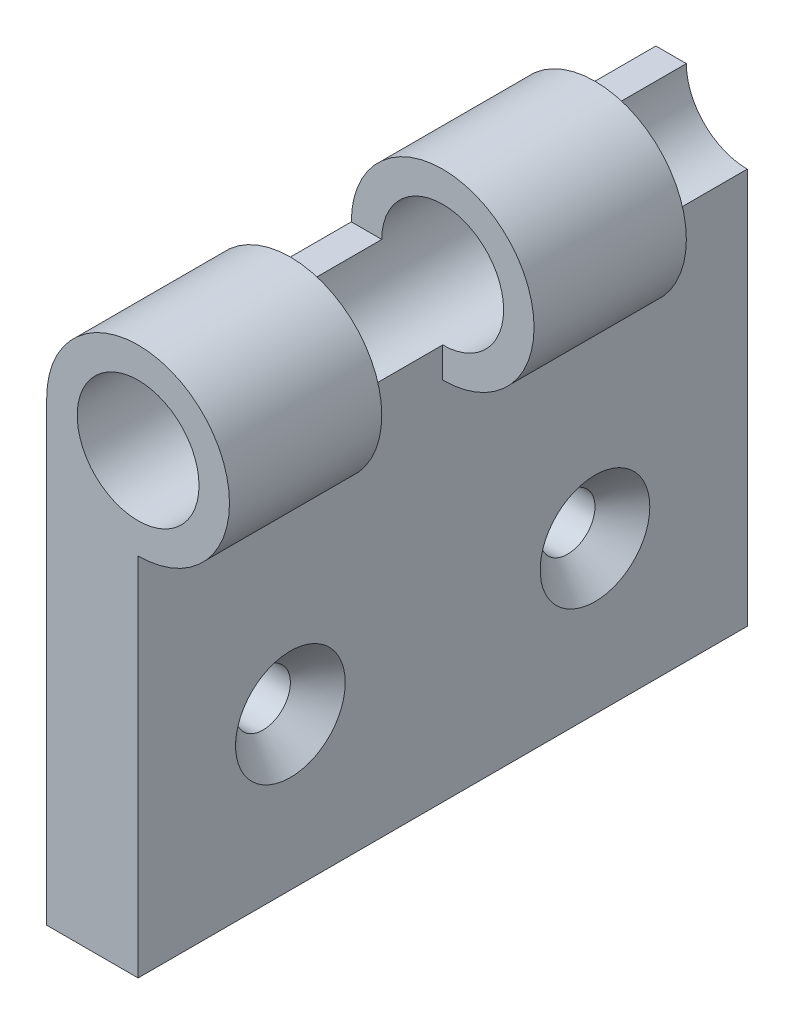
SolidWorks part; units mm, degrees
ref_plane "Front Plane" through (0, 0, 0) normal (0, 0, 1) x (1, 0, 0)
ref_plane "Top Plane" through (0, 0, 0) normal (0, 1, 0) x (1, 0, 0)
ref_plane "Right Plane" through (0, 0, 0) normal (1, 0, 0) x (0, 0, -1)
sketch "Sketch1" plane through (0, 0, 0) normal (0, 0, 1) x (1, 0, 0)
  line L1 (0, 0) -> (3, 0)
  line L2 (0, 0) -> (0, -15)
  line L3 (0, -15) -> (3, -15)
  line L4 (3, 0) -> (3, -15)
  dimension "D1" = 3
  dimension "D2" = 15
extrude "Boss-Extrude1" add sketch "Sketch1" against normal blind 20
sketch "Sketch2" plane through (0, 0, 0) normal (0, 0, 1) x (1, 0, 0)
  circle A0 centre (3, 0) radius 3
  dimension "D1" = 6
extrude "Boss-Extrude2" add sketch "Sketch2" against normal blind 5
pattern_linear "LPattern2" count 2 spacing 10 along (0, 0, -1) of "Boss-Extrude2"
sketch "Sketch3" plane through (0, 0, 0) normal (0, 0, 1) x (1, 0, 0)
  circle A0 centre (3, 0) radius 2
  dimension "D1" = 4
  dimension "D2" = 3
extrude "Cut-Extrude1" cut sketch "Sketch3" against normal through all both and the other way through all
hole_wizard "CSK for M1.6 Countersunk Flat Head Screw1" positions "Sketch5" profile "Sketch6" countersink size "M1.6" standard "ISO"
sketch "Sketch5" plane through (3, 0, 0) normal (1, 0, 0) x (0, 0, -1)
  line L0 (0, -15) -> (0, -3) construction
  line L1 (20, -15) -> (0, -15) construction
  point P0 (5, -10)
  point P6 (15, -10)
  dimension "D1" = 5
  dimension "D2" = 10
  dimension "D3" = 5
sketch "Sketch6" plane through (3, -10, -5) normal (0, 1, 0) x (0, 0, -1)
  line L0 (0, 0) -> (0, 3.5408)
  line L1 (0, 3.5408) -> (0.9, 3)
  line L2 (0.9, 3) -> (0.9, 0.9)
  line L3 (0.9, 0.9) -> (1.8, 0)
  line L5 (1.8, 0) -> (0, 0)
  line L6 (-0.9, 0.9) -> (-1.8, 0) construction
  line L10 (0, 3.5408) -> (-0.9, 3) construction
  line L11 (0, -6.35) -> (0, 107.95) construction
  dimension "Hole Dia." = 1.8
  dimension "Hole Depth" = 3
  dimension "Near C'Sink Dia." = 3.6
  dimension "Near C'Sink Angle" = 90
  dimension "Drill Angle" = 118
